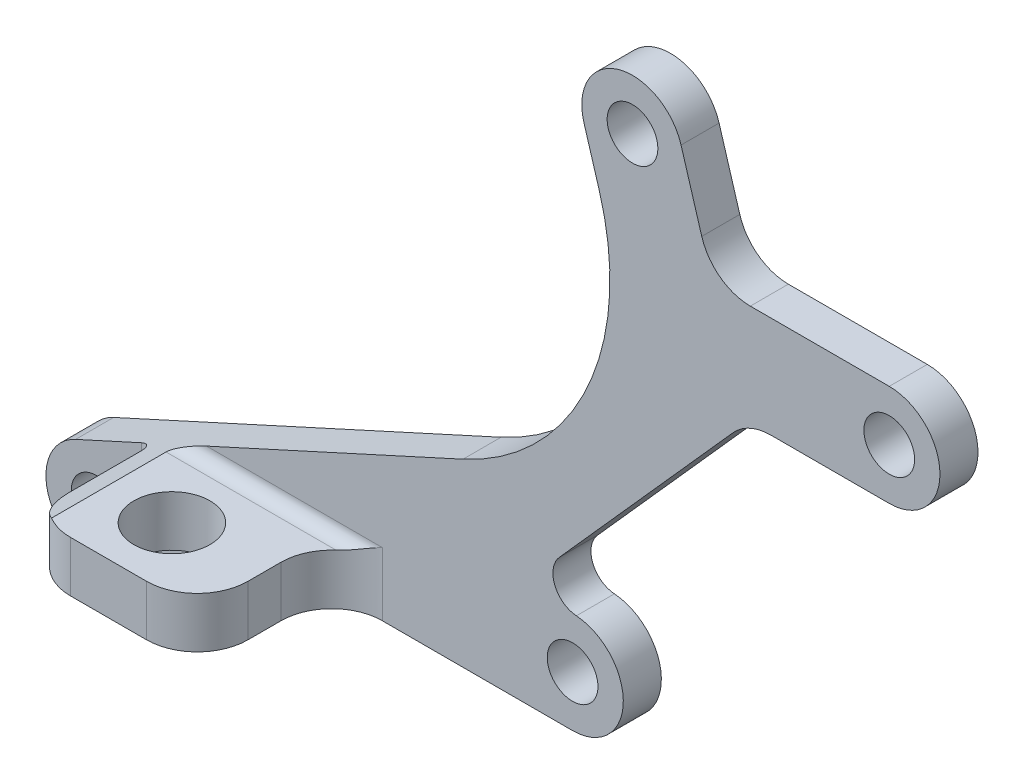
SolidWorks part; units mm, degrees
ref_plane "Plan de face" through (0, 0, 0) normal (0, 0, 1) x (1, 0, 0)
ref_plane "Plan de dessus" through (0, 0, 0) normal (0, 1, 0) x (1, 0, 0)
ref_plane "Plan de droite" through (0, 0, 0) normal (1, 0, 0) x (0, 0, -1)
sketch "Esquisse1" plane through (0, 0, 0) normal (0, 0, 1) x (1, 0, 0)
  line L0 (5.7259, 0) -> (16, 0)
  line L2 (16, 4.0012) -> (14, 4.0012)
  line L3 (14, 4.0012) -> (22.9191, 14.0012)
  line L4 (22.9191, 14.0012) -> (28.4872, 14.0012)
  line L6 (28.4872, 18.0012) -> (21.5221, 18.0012)
  line L11 (16, 2.0006) -> (28.4872, 16.0012) construction
  line L12 (-3.5973, 0.147) -> (11.6789, 7.1087)
  line L15 (17.0539, 18.9689) -> (16.4475, 20.9852)
  line L17 (-5.2384, -0.381) -> (1.3589, 2.6254) construction
  line L18 (-1.9386, -3.4928) -> (5.7259, 0)
  line L20 (20.2779, 22.1373) -> (21.5221, 18.0012)
  arc A0 (28.4872, 14.0012) -> (28.4872, 18.0012) centre (28.4872, 16.0012) ccw
  arc A2 (16, 0) -> (16, 4.0012) centre (16, 2.0006) ccw
  circle A5 centre (28.4872, 16.0012) radius 1
  circle A6 centre (16, 2.0006) radius 1
  arc A9 (20.2779, 22.1373) -> (16.4475, 20.9852) centre (18.3627, 21.5613) ccw
  circle A10 centre (18.3627, 21.5613) radius 1
  arc A14 (11.6789, 7.1087) -> (17.0539, 18.9689) centre (7.5735, 16.1173) ccw
  arc A15 (-3.5973, 0.147) -> (-1.9386, -3.4928) centre (-2.768, -1.6729) ccw
  circle A16 centre (-2.768, -1.6729) radius 1
  dimension "D14" = 10
  dimension "D15" = 2
  dimension "D16" = 2
  dimension "D2" = 4
  dimension "D4" = 3.5601
  dimension "D11" = 2
  dimension "D12" = 3.1593
  dimension "D5" = 2
  dimension "D3" = 4
  dimension "D8" = 48.27
  dimension "D18" = 6.9652
  dimension "D19" = 4
extrude "Boss.-Extru.1" add sketch "Esquisse1" along normal blind 1.5
fillet "Congé1" radius 2 2 edges at (22.9191, 14.0012, 0.75) (21.5221, 18.0012, 0.75)
fillet "Congé2" radius 1 1 edges at (14, 4.0012, 0.75)
sketch "Esquisse2" plane through (0, 0, 0) normal (0, 0, -1) x (-1, 0, 0)
  line L1 (-5.7259, 0) -> (-16, 0) construction
  line L9 (-6.5, 0) -> (0.5, 0)
  line L14 (-6.5, 0) -> (-6.5, 2)
  line L15 (-6.5, 2) -> (0.5, 2)
  line L16 (0.5, 0) -> (0.5, 2)
  arc A0 (-16.1496, 3.9956) -> (-16, 0) centre (-16, 2.0006) ccw construction
  dimension "D1" = 2
  dimension "D2" = 7
  dimension "D3" = 9.5
extrude "Boss.-Extru.2" add sketch "Esquisse2" against normal blind 6.8
fillet "Congé3" radius 0.5 1 edges at (3.4844, 2, 1.5)
fillet "Congé4" radius 0.5 1 edges at (-0.5, 0.7793, 1.5)
fillet "Congé5" radius 2 1 edges at (6.5, 1.25, 1.5)
fillet "Congé6" radius 2 2 edges at (-0.5, 1, 6.8) (6.5, 1, 6.8)
sketch "Esquisse3" plane through (0, 2, 0) normal (0, 1, 0) x (1, 0, 0)
  line L2 (6.5, -4.8) -> (6.5, -3.5) construction
  line L3 (1.5, -6.8) -> (4.5, -6.8) construction
  circle A0 centre (3, -4.3) radius 1.5
  dimension "D1" = 3
  dimension "D2" = 3.5
  dimension "D3" = 2.5
extrude "Enlèv. mat.-Extru.1" cut sketch "Esquisse3" against normal blind 5
fillet "Congé7" radius 5 1 edges at (5.7259, 0, 0.75)
sketch "Esquisse4" plane through (0, 0, 0) normal (0, 0, -1) x (-1, 0, 0)
  line L0 (0.5, 2) -> (-0.4687, 2)
  line L1 (-0.4687, 2) -> (0.5, 1.5585)
  line L2 (0.5, 1.5585) -> (0.5, 2)
extrude "Enlèv. mat.-Extru.2" cut sketch "Esquisse4" against normal blind 7
